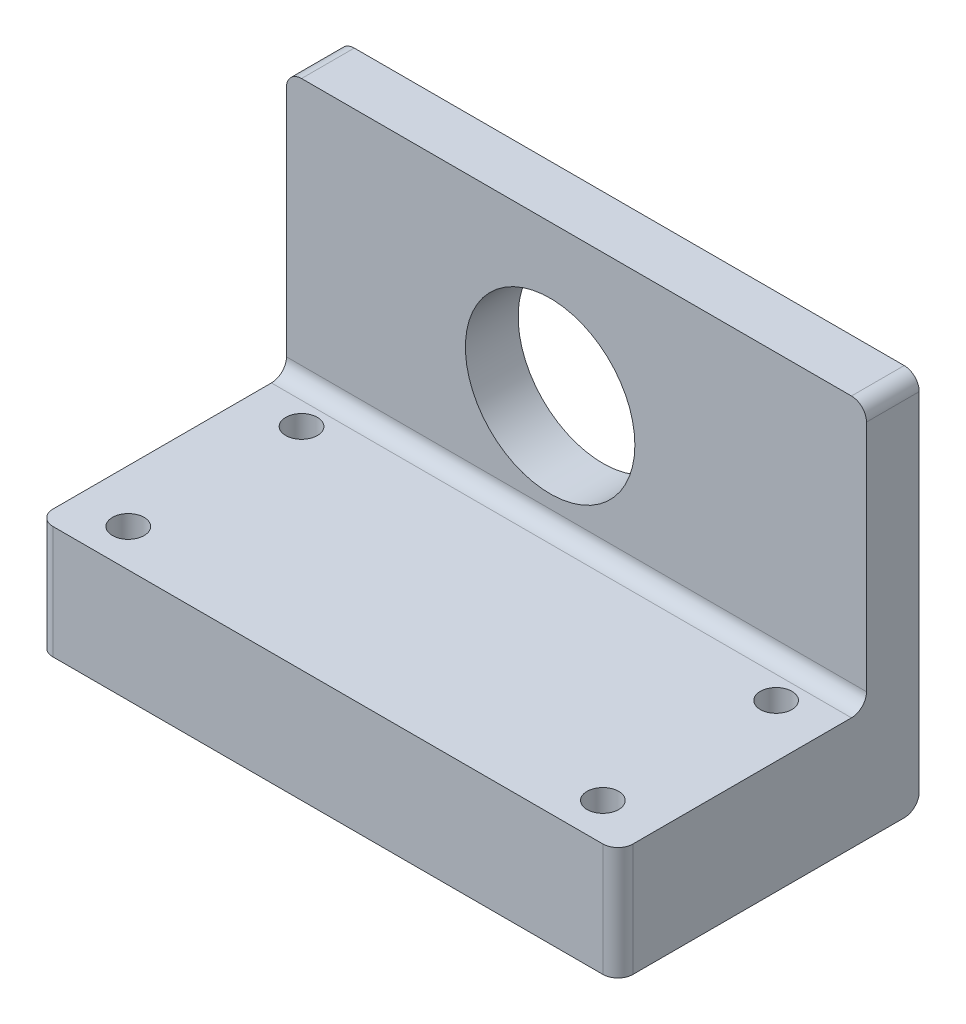
SolidWorks part; units mm, degrees
ref_plane "Front Plane" through (0, 0, 0) normal (0, 0, 1) x (1, 0, 0)
ref_plane "Top Plane" through (0, 0, 0) normal (0, 1, 0) x (1, 0, 0)
ref_plane "Right Plane" through (0, 0, 0) normal (1, 0, 0) x (0, 0, -1)
sketch "Sketch1" plane through (0, 0, 0) normal (0, 0, 1) x (1, 0, 0)
  line L1 (-35, 17.5) -> (42, 17.5)
  line L2 (-35, 17.5) -> (-35, -17.5)
  line L3 (-35, -17.5) -> (42, -17.5)
  line L4 (42, 17.5) -> (42, -17.5)
  dimension "D1" = 77
  dimension "D2" = 35
  dimension "D3" = 17.5
  dimension "D4" = 35
extrude "Boss-Extrude1" add sketch "Sketch1" along normal blind 7
sketch "Sketch2" plane through (0, 0, 7) normal (0, 0, 1) x (1, 0, 0)
  line L2 (42, -17.5) -> (42, 17.5) construction
  line L3 (42, 17.5) -> (-35, 17.5) construction
  circle A0 centre (0, -2.5) radius 11.25
  dimension "D1" = 42
  dimension "D2" = 22.5
  dimension "D3" = 20
extrude "Cut-Extrude1" cut sketch "Sketch2" against normal blind 15
sketch "Sketch3" plane through (0, 0, 0) normal (0, 0, -1) x (-1, 0, 0)
  line L0 (35, 17.5) -> (35, -17.5) construction
  line L1 (-42, -17.5) -> (35, -17.5)
  line L2 (-42, -17.5) -> (-42, -32.5)
  line L3 (-42, -32.5) -> (35, -32.5)
  line L4 (35, -17.5) -> (35, -32.5)
  dimension "D1" = 15
extrude "Boss-Extrude2" add sketch "Sketch3" against normal blind 40
sketch "Sketch4" plane through (0, -17.5, 0) normal (0, 1, 0) x (1, 0, 0)
  line L0 (42, -40) -> (42, -7) construction
  line L1 (-35, -40) -> (-35, -7) construction
  line L2 (-35, -40) -> (42, -40) construction
  line L3 (-35, -7) -> (42, -7) construction
  circle A0 centre (-28, -35) radius 2.1
  circle A1 centre (-28, -12) radius 2.1
  circle A2 centre (35, -35) radius 2.1
  circle A3 centre (35, -12) radius 2.1
  dimension "D1" = 4.2
  dimension "D2" = 4.2
  dimension "D3" = 4.2
  dimension "D4" = 4.2
  dimension "D5" = 7
  dimension "D6" = 7
  dimension "D7" = 7
  dimension "D8" = 7
  dimension "D9" = 5
  dimension "D10" = 5
  dimension "D11" = 5
extrude "Cut-Extrude2" cut sketch "Sketch4" against normal blind 20
fillet "Fillet1" radius 2 1 edges at (3.5, -17.5, 7)
fillet "Fillet2" radius 2 5 edges at (-35, 17.5, 3.5) (42, 17.5, 3.5) (42, -25, 40) (-35, -25, 40) (3.5, -32.5, 0)
